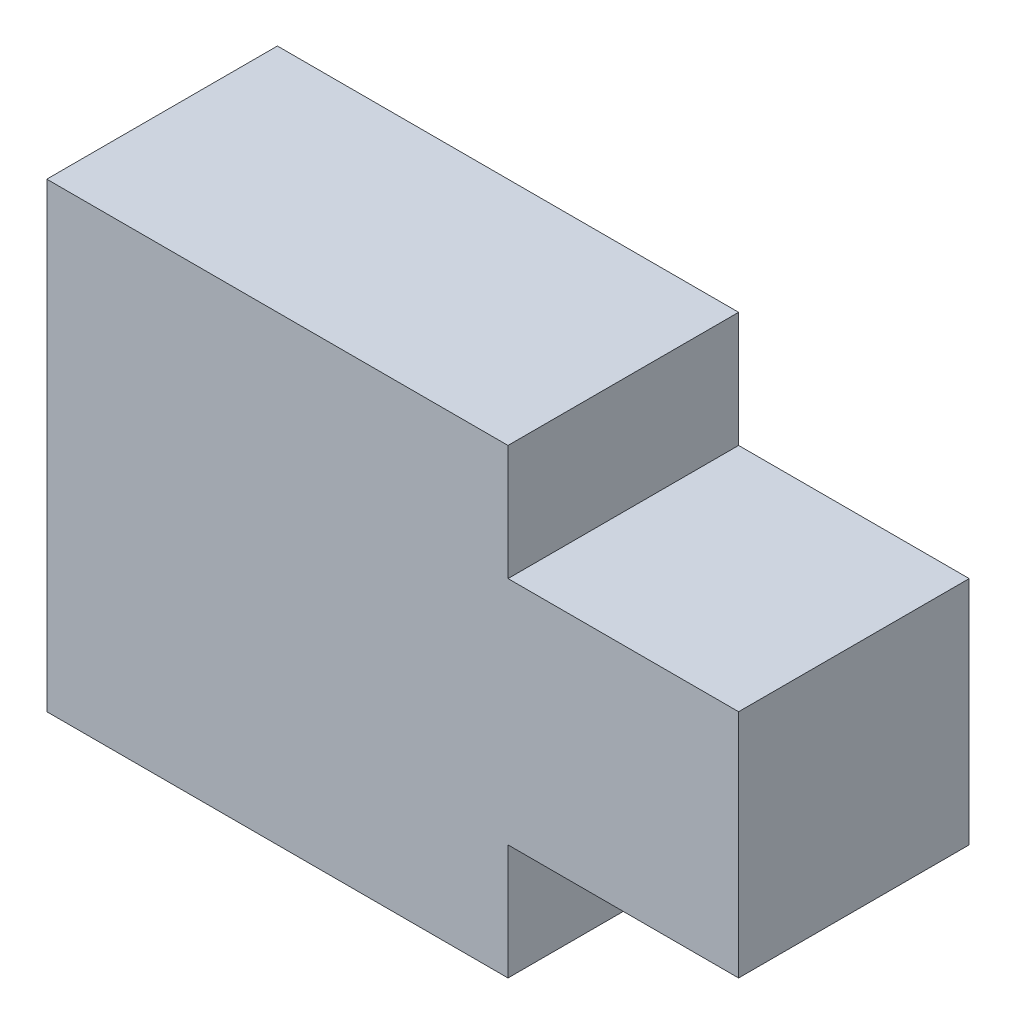
SolidWorks part; units mm, degrees
ref_plane "Piano frontale" through (0, 0, 0) normal (0, 0, 1) x (1, 0, 0)
ref_plane "Piano superiore" through (0, 0, 0) normal (0, 1, 0) x (1, 0, 0)
ref_plane "Piano destro" through (0, 0, 0) normal (1, 0, 0) x (0, 0, -1)
sketch "Schizzo1" plane through (0, 0, 0) normal (0, 0, 1) x (1, 0, 0)
  line L0 (0, 0) -> (0, 100)
  line L1 (0, 100) -> (100, 100)
  line L2 (100, 100) -> (100, 75)
  line L3 (100, 75) -> (150, 75)
  line L4 (150, 75) -> (150, 25)
  line L5 (150, 25) -> (100, 25)
  line L6 (100, 25) -> (100, 0)
  line L7 (100, 0) -> (0, 0)
  line L8 (0, 50) -> (100, 50)
  line L9 (50, 100) -> (50, 0)
  line L10 (100, 25) -> (100, 75)
  point P13 (101.8467, 50)
  point P14 (100, 50)
  dimension "D1" = 100
  dimension "D2" = 100
  dimension "D3" = 50
  dimension "D4" = 50
extrude "Estrusione-Estrusione1" add sketch "Schizzo1" along normal blind 50 contours L9 L1 L0 L8 | L9 L8 L0 L7 | L6 L10 L8 L9 L7 | L8 L10 L2 L1 L9 | L10 L5 L4 L3
